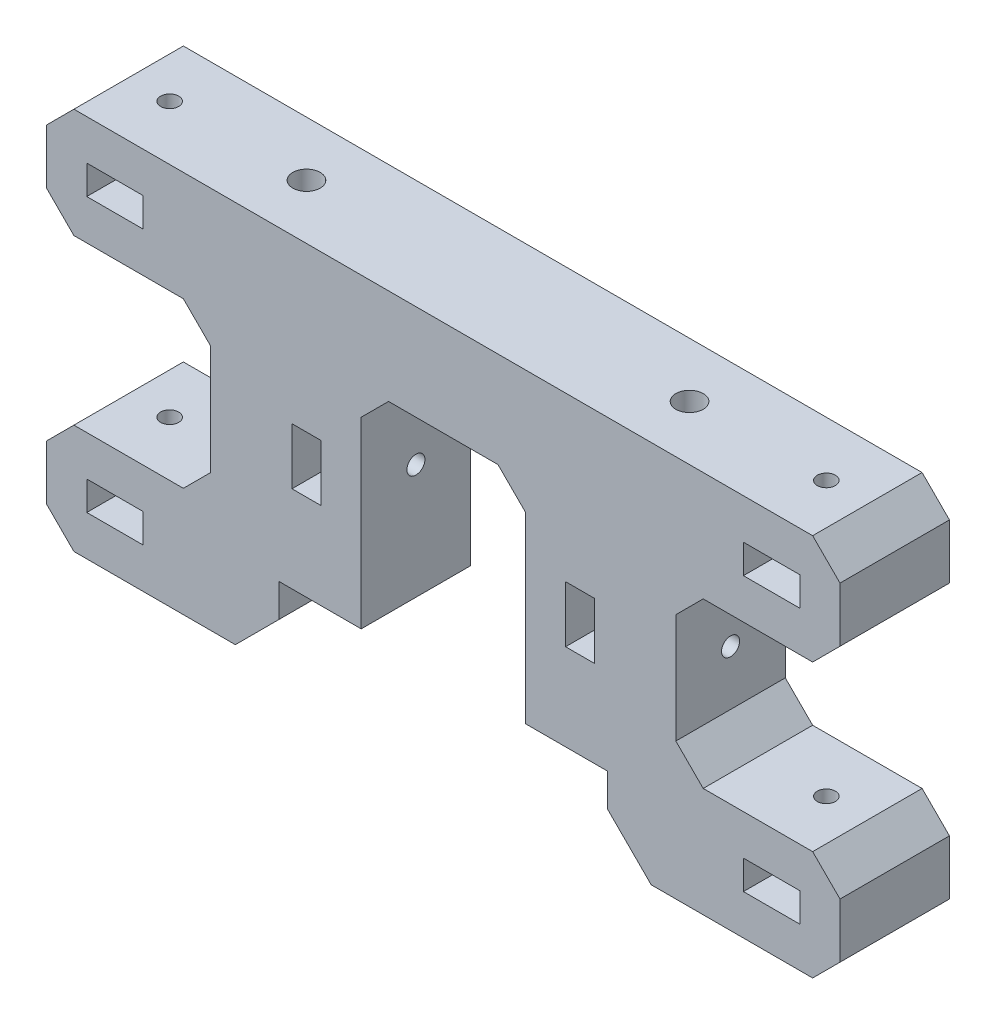
SolidWorks part; units mm, degrees
ref_plane "前基準面" through (0, 0, 0) normal (0, 0, 1) x (1, 0, 0)
ref_plane "上基準面" through (0, 0, 0) normal (0, 1, 0) x (1, 0, 0)
ref_plane "右基準面" through (0, 0, 0) normal (1, 0, 0) x (0, 0, -1)
sketch "草圖1" plane through (0, 0, 0) normal (0, 0, 1) x (1, 0, 0)
  line L0 (15, 17.5) -> (15, -35)
  line L1 (72.5, -35) -> (15, -35)
  line L2 (72.5, -15) -> (72.5, -35)
  line L3 (42.5, -15) -> (72.5, -15)
  line L4 (42.5, 15) -> (42.5, -15)
  line L5 (-15, 17.5) -> (15, 17.5)
  line L6 (-42.5, 15) -> (-72.5, 15)
  line L7 (-72.5, 15) -> (-72.5, 35)
  line L8 (-72.5, 35) -> (72.5, 35)
  line L9 (72.5, 35) -> (72.5, 15)
  line L10 (72.5, 15) -> (42.5, 15)
  line L11 (-42.5, 0) -> (42.5, 0) construction
  line L12 (-72.5, 25) -> (72.5, 25) construction
  line L13 (-54.85, -27.65) -> (-54.85, -22.35)
  line L14 (-65.15, 27.65) -> (-54.85, 27.65)
  line L15 (-65.15, 27.65) -> (-65.15, 22.35)
  line L16 (0, 8.4883) -> (0, -55.6825) construction
  line L17 (-65.15, 22.35) -> (-54.85, 22.35)
  line L18 (-54.85, 27.65) -> (-54.85, 22.35)
  line L19 (-65.15, -22.35) -> (-54.85, -22.35)
  line L20 (-65.15, -27.65) -> (-65.15, -22.35)
  line L21 (-65.15, -27.65) -> (-54.85, -27.65)
  line L22 (-25, 5.15) -> (-25, -5.15) construction
  line L23 (-27.65, 5.15) -> (-22.35, 5.15)
  line L24 (-27.65, 5.15) -> (-27.65, -5.15)
  line L25 (-27.65, -5.15) -> (-22.35, -5.15)
  line L26 (-22.35, 5.15) -> (-22.35, -5.15)
  line L27 (65.15, -27.65) -> (54.85, -27.65)
  line L28 (65.15, -27.65) -> (65.15, -22.35)
  line L29 (65.15, -22.35) -> (54.85, -22.35)
  line L30 (54.85, -27.65) -> (54.85, -22.35)
  line L31 (25, 5.15) -> (25, -5.15) construction
  line L32 (22.35, 5.15) -> (22.35, -5.15)
  line L33 (27.65, -5.15) -> (22.35, -5.15)
  line L34 (-60, 0.4263) -> (-60, -6.8737) construction
  line L35 (27.65, 5.15) -> (27.65, -5.15)
  line L36 (27.65, 5.15) -> (22.35, 5.15)
  line L37 (-42.5, 15) -> (-42.5, -15)
  line L38 (-42.5, -15) -> (-72.5, -15)
  line L39 (-72.5, -15) -> (-72.5, -35)
  line L40 (-72.5, -35) -> (-15, -35)
  line L41 (-15, 17.5) -> (-15, -35)
  line L42 (54.85, 27.65) -> (54.85, 22.35)
  line L43 (65.15, 22.35) -> (54.85, 22.35)
  line L44 (65.15, 27.65) -> (65.15, 22.35)
  line L45 (65.15, 27.65) -> (54.85, 27.65)
  point P13 (0, 0)
  point P20 (-65.15, 25)
  point P21 (-60, 27.65)
  point P26 (-60, -27.65)
  point P27 (-65.15, -25)
  point P32 (-27.65, 0)
  point P33 (-25, 5.15)
  point P40 (65.15, -25)
  point P41 (60, -27.65)
  point P58 (27.65, 0)
  point P63 (60, 27.65)
  point P64 (65.15, 25)
  dimension "D1" = 20
  dimension "D2" = 57.5
  dimension "D3" = 30
  dimension "D4" = 60
  dimension "D5" = 30
  dimension "D6" = 17.5
  dimension "D7" = 10.3
  dimension "D8" = 5.3
  dimension "D9" = 25
extrude "填料-伸長2" add sketch "草圖1" along normal blind 20
chamfer "導角1" distance 5 angle 45 14 edges at (15, 17.5, 10) (-15, 17.5, 10) (72.5, -35, 10) (72.5, -15, 10) (42.5, -15, 10) (42.5, 15, 10) (72.5, 15, 10) (72.5, 35, 10) (-72.5, -35, 10) (-72.5, -15, 10) (-42.5, -15, 10) (-42.5, 15, 10) (-72.5, 15, 10) (-72.5, 35, 10)
ref_plane "右側軌道平面" through (60, 0, 0) normal (1, 0, 0) x (0, 0, -1)
ref_plane "z中心面" through (0, 0, 10) normal (0, 0, 1) x (1, 0, 0)
sketch "草圖2" plane through (0, 35, 0) normal (0, 1, 0) x (1, 0, 0)
  line L1 (-38.5, -10) -> (38.5, -10) construction
  line L2 (60, -39.6824) -> (60, 39.6824) construction
  circle A0 centre (60, -10) radius 1.65
  dimension "D1" = 3.3
extrude "除料-伸長1" cut sketch "草圖2" against normal up to surface (50 mm away) contours A0
sketch "草圖4" plane through (42.5, 0, 0) normal (1, 0, 0) x (0, 0, -1)
  line L0 (-10, 38.5) -> (-10, -38.5) construction
  line L1 (11, 0) -> (-11, 0) construction
  circle A0 centre (-10, 0) radius 1.65
  dimension "D1" = 3.3
extrude "除料-伸長2" cut sketch "草圖4" against normal up to surface (57.5 mm away) contours A0
mirror "鏡射1" about plane through (0, 0, 0) normal (0, 1, 0) of "除料-伸長1"
mirror "鏡射2" about plane through (0, 0, 0) normal (1, 0, 0) of "鏡射1", "除料-伸長2", "除料-伸長1"
ref_plane "平面3" through (35, 0, 0) normal (1, 0, 0) x (0, 0, -1)
sketch "草圖7" plane through (0, 35, 0) normal (0, 1, 0) x (1, 0, 0)
  line L0 (35, -11) -> (35, 11) construction
  line L1 (-38.5, -10) -> (38.5, -10) construction
  circle A0 centre (35, -10) radius 2.5
  dimension "D1" = 5
extrude "除料-伸長4" cut sketch "草圖7" against normal blind 15 contours A0
mirror "鏡射9" about plane through (0, 0, 0) normal (1, 0, 0) of "除料-伸長4"
sketch "草圖10" plane through (0, 0, 20) normal (0, 0, 1) x (1, 0, 0)
  line L0 (15, -35) -> (15, -21)
  line L1 (15, 12.5) -> (15, -35) construction
  line L2 (15, -21) -> (30, -21)
  line L3 (30, -21) -> (30, -27)
  line L4 (30, -27) -> (30, -35) construction
  line L5 (15, -35) -> (67.5, -35) construction
  line L6 (30, -35) -> (15, -35)
  line L7 (30, -35) -> (38, -35)
  line L8 (30, -27) -> (38, -35)
  dimension "D1" = 15
  dimension "D2" = 6
  dimension "D3" = 8
extrude "除料-伸長7" cut sketch "草圖10" against normal up to next
sketch "草圖11" plane through (0, -21, 0) normal (0, -1, 0) x (-1, 0, 0)
  line L0 (-22.5, -20) -> (-22.5, 0) construction
  line L1 (-30, -20) -> (-15, -20) construction
  line L2 (-30, 0) -> (-15, 0) construction
  line L3 (-38.5, -10) -> (38.5, -10) construction
  circle A0 centre (-22.5, -10) radius 2.5
  dimension "D1" = 5
extrude "除料-伸長8" cut sketch "草圖11" against normal blind 10
mirror "鏡射10" about plane through (0, 0, 0) normal (1, 0, 0) of "除料-伸長8", "除料-伸長7"
